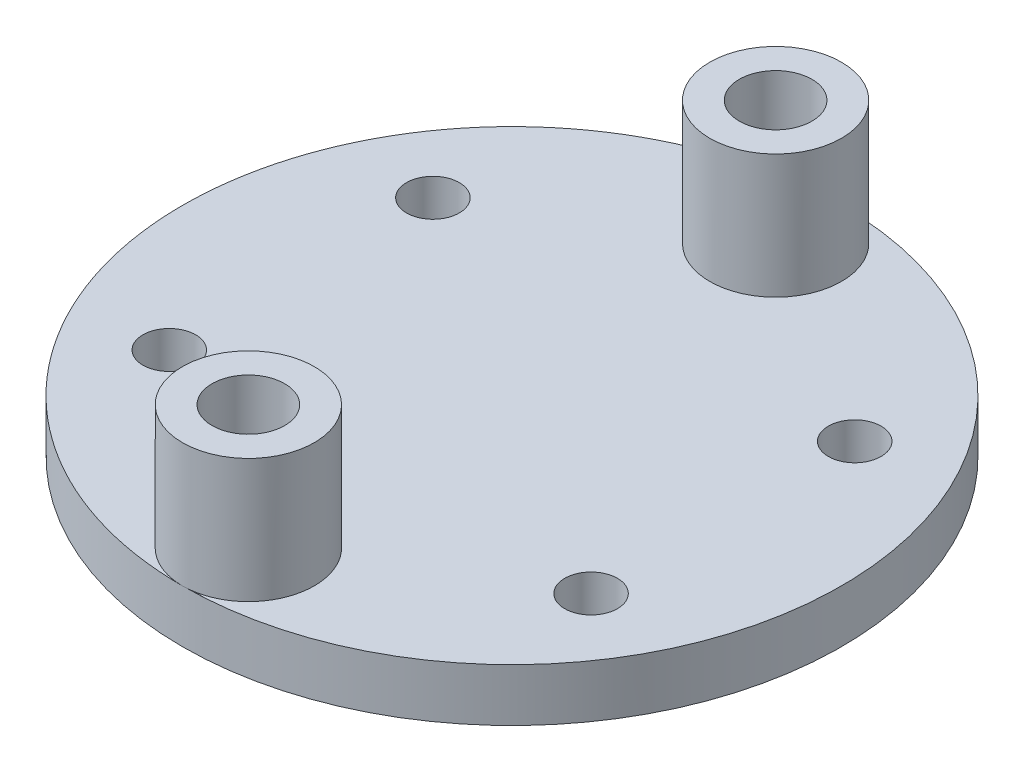
SolidWorks part; units mm, degrees
material "PLA"
ref_plane "Front Plane" through (0, 0, 0) normal (0, 0, 1) x (1, 0, 0)
ref_plane "Top Plane" through (0, 0, 0) normal (0, 1, 0) x (1, 0, 0)
ref_plane "Right Plane" through (0, 0, 0) normal (1, 0, 0) x (0, 0, -1)
sketch "Sketch1" plane through (0, 0, 0) normal (0, 1, 0) x (1, 0, 0)
  line L0 (0, 8.89) -> (25.4, 8.89) construction
  line L5 (0, 0) -> (25.4, 0)
  line L6 (0, 0) -> (0, 17.78)
  line L7 (0, 17.78) -> (25.4, 17.78)
  line L8 (25.4, 0) -> (25.4, 17.78)
  line L9 (12.7, 17.78) -> (12.7, 0) construction
  circle A2 centre (2.54, 15.24) radius 1.27
  circle A3 centre (22.86, 15.24) radius 1.27
  circle A4 centre (22.86, 2.54) radius 1.27
  circle A5 centre (2.54, 2.54) radius 1.27
  circle A6 centre (12.7, 8.89) radius 15.875
  circle A7 centre (12.7, 21.59) radius 1.75
  circle A8 centre (12.7, -3.81) radius 1.75
  dimension "D3" = 2.54
  dimension "D6" = 31.75
  dimension "D7" = 3.5
  dimension "D1" = 17.78
  dimension "D2" = 25.4
  dimension "D4" = 20.32
  dimension "D5" = 12.7
  dimension "D8" = 12.7
extrude "Boss-Extrude1" add sketch "Sketch1" along normal blind 2.54 contours L5 L8 L7 L6 A3 A2 A4 A5 | A6 L8 L5 L6 L7 A7 A8
sketch "Sketch2" plane through (0, 2.54, 0) normal (0, 1, 0) x (1, 0, 0)
  circle A0 centre (12.7, -3.81) radius 1.75 construction
  circle A1 centre (12.7, 8.89) radius 15.875
  circle A2 centre (12.7, 8.89) radius 15.875
  circle A3 centre (12.7, 21.59) radius 1.75 construction
  circle A4 centre (12.7, -3.81) radius 1.75
  circle A5 centre (12.7, 21.59) radius 1.75
  circle A6 centre (12.7, 21.59) radius 3.175
  circle A7 centre (12.7, -3.81) radius 3.175
  circle M8 centre (12.7, 21.59) radius 1.75
  circle M9 centre (12.7, -3.81) radius 1.75
  dimension "D1" = 0
extrude "Boss-Extrude2" add sketch "Sketch2" along normal blind 5.975 contours A6 M8 | A7 M9
